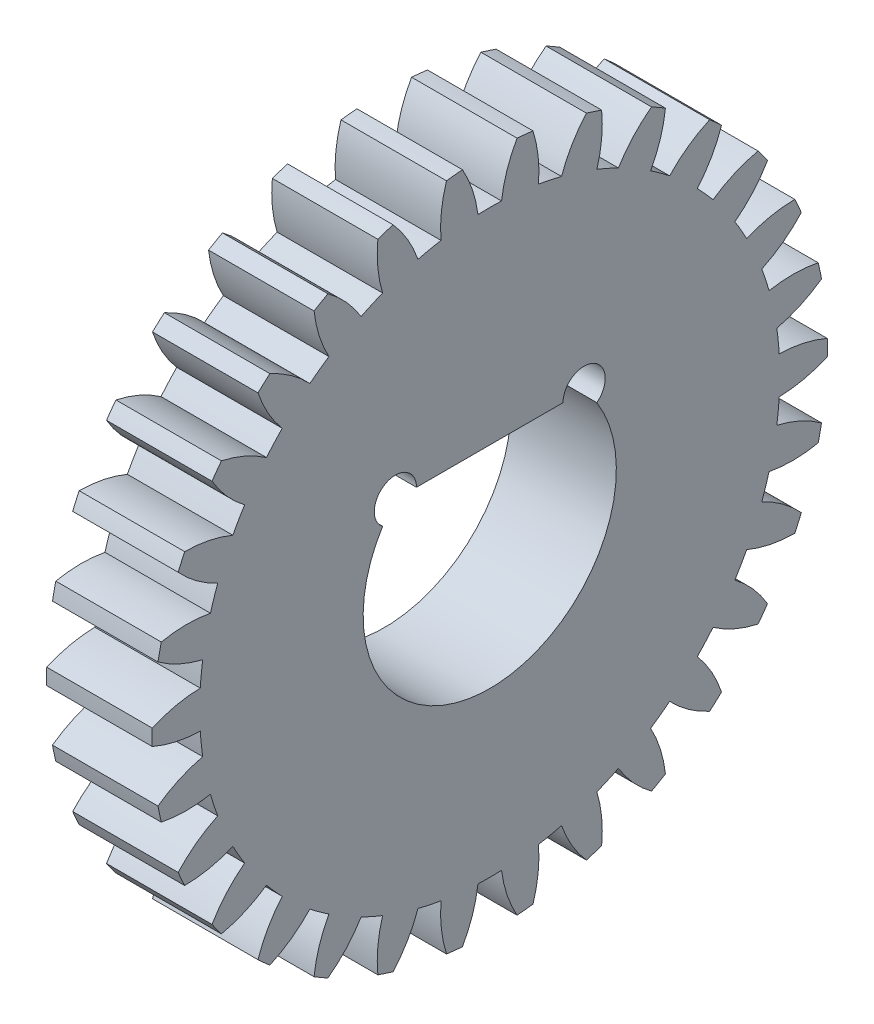
SolidWorks part; units mm, degrees
ref_plane "Plane1" through (0, 0, 0) normal (0, 0, 1) x (1, 0, 0)
ref_plane "Plane2" through (0, 0, 0) normal (0, 1, 0) x (1, 0, 0)
ref_plane "Plane3" through (0, 0, 0) normal (1, 0, 0) x (0, 0, -1)
sketch "HoldingSke" plane through (0, 0, 0) normal (0, 1, 0) x (1, 0, 0)
  line L0 (0, 0) -> (1.7321, -1)
  line L1 (-15, 0) -> (100, 0) construction
  line L2 (0, 0) -> (-2.1039, 2.3779)
  line L3 (0, 0) -> (-11.863, 4.5341)
  line L4 (0, 0) -> (7.479, 4.318)
  line L5 (0, 0) -> (-46.8476, -17.4728)
  line L6 (0, 0) -> (-2.0724, -1.3983)
  line L7 (-2.1039, 2.3779) -> (8.6586, 51.2059)
  line L8 (-76.2, 54.61) -> (-75.2, 54.61)
  line L9 (-67.7845, 28.3722) -> (-49.3413, 33.142)
  line L10 (-76.2, 71.12) -> (104.1128, 71.12)
  line L11 (0, 0) -> (-2.5, 0)
  line L12 (-76.2, 101.6) -> (-76.181, 101.6)
  line L13 (24.9733, 27.94) -> (52.9518, 28.4284)
  line L14 (24.9733, 27.94) -> (24.9743, 27.94)
  line L15 (24.9733, 27.94) -> (100.4006, 29.5858)
  line L16 (-63.627, -0.5) -> (-12.827, -0.5)
  circle A0 centre (0, 0) radius 3
  circle A1 centre (0, 0) radius 6.874
  circle A2 centre (0, 0) radius 37.5
  circle A3 centre (0, 0) radius 3
  dimension "MHD" = 13.748
  dimension "Hub_dia" = 75
  dimension "Bore" = 6
  dimension "MBD" = 6
  dimension "Num_teeth" = 30
  dimension "Pitch" = 2
  dimension "Overall_len" = 50
  dimension "Show_teeth" = 30
  dimension "Thickness" = 2.5
  dimension "OAL" = 50.0001
  dimension "T_dim" = 1
  dimension "Ap" = 14.5
  dimension "H" = 19.05
  dimension "Pitch_radius" = 180.3128
  dimension "Width" = 2.5
  dimension "Backlash" = 0.019
  dimension "Addendum_fac" = 1
  dimension "Dedendum_fac" = 1.25
  dimension "Clearance_fac" = 0.25
  dimension "Dedendum_add" = 0.001
  dimension "Module" = 0.5
sketch "BasProSke" plane through (0, 0, 0) normal (0, 1, 0) x (1, 0, 0)
  line L0 (-10, 0) -> (60, 0) construction
  line L1 (0, 0) -> (0, 8)
  line L2 (0, 0) -> (2.5, 0)
  line L3 (2.5, 0) -> (2.5, 8)
  line L4 (2.5, 8) -> (0, 8)
  dimension "Thickness" = 2.5
  dimension "Diameter" = 16
revolve "Base-Revolve" add sketch "BasProSke" angle 360 about L0
sketch "TooCutSke" plane through (0, 0, 0) normal (1, 0, 0) x (0, 0, -1)
  line L1 (0, 0) -> (0, 107) construction
  line L2 (0, 0) -> (-0.4258, 7.4879) construction
  line L3 (0, 0) -> (-1.5661, 14.9007) construction
  line L4 (-0.4258, 7.4879) -> (-0.7831, 7.4504) construction
  arc A0 (0.279, 6.8683) -> (-0.279, 6.8683) centre (0, 0) ccw
  arc A1 (0.6614, 7.9981) -> (-0.6614, 7.9981) centre (0, 0) ccw
  circle A2 centre (0, 0) radius 7.5 construction
  circle A3 centre (0, 0) radius 7.2611 construction
  arc A4 (-0.279, 6.8683) -> (-0.6614, 7.9981) centre (-3.2551, 6.4906) ccw
  arc A5 (0.6614, 7.9981) -> (0.279, 6.8683) centre (3.2551, 6.4906) ccw
  dimension "Root_dia" = 13.748
  dimension "Overcut_dia" = 16.0508
  dimension "Pitch_dia" = 15
  dimension "Base_dia" = 14.5222
  dimension "Flank_rad" = 3
  dimension "Half_ang" = 6
  dimension "Half_CT" = 0.3593
extrude "ToothCut" cut sketch "TooCutSke" along normal through all
fillet "Breaks" [suppressed] radius 0.01
fillet "RootFillets" [suppressed] radius 0.126
pattern_circular "TeethCuts" count 30 every 12 about axis through (-10, 0, 0) along (1, 0, 0) of "ToothCut", "RootFillets", "Breaks"
sketch "HubNeaOneSke" plane through (0, 0, 0) normal (-1, 0, 0) x (0, 0, 1)
  circle A0 centre (0, 0) radius 6.874
  dimension "Diameter" = 13.748
extrude "HubNearOne" [suppressed] add sketch "HubNeaOneSke" along normal blind 47.5001
sketch "HubNeaBotSke" plane through (0, 0, 0) normal (-1, 0, 0) x (0, 0, 1)
  circle A0 centre (0, 0) radius 6.874
  dimension "Diameter" = 13.748
extrude "HubNearBoth" [suppressed] add sketch "HubNeaBotSke" along normal blind 23.75
ref_plane "FarPln" through (2.5, 0, 0) normal (1, 0, 0) x (0, 0, -1)
sketch "HubFarSke" plane through (2.5, 0, 0) normal (1, 0, 0) x (0, 0, -1)
  circle A0 centre (0, 0) radius 6.874
  dimension "Diameter" = 13.748
extrude "HubFar" [suppressed] add sketch "HubFarSke" along normal blind 23.75
sketch "BorSke" plane through (0, 0, 0) normal (1, 0, 0) x (0, 0, -1)
  circle A0 centre (0, 0) radius 3
  dimension "Diameter" = 6
extrude "Bore" cut sketch "BorSke" along normal mid plane 100.0001
sketch "KeySke" plane through (0, 0, 0) normal (1, 0, 0) x (0, 0, -1)
  line L0 (-1, 0) -> (-1, 4)
  line L1 (-1, 4) -> (1, 4)
  line L2 (1, 4) -> (1, 0)
  line L3 (0, 0) -> (0, 34) construction
  line L4 (-1, 0) -> (1, 0)
  dimension "Offset" = 4
  dimension "Width" = 2
extrude "Keyway" [suppressed] cut sketch "KeySke" along normal mid plane 100.0001
pattern_circular "Keyway2" [suppressed] count 2 every 90 about axis through (-10, 0, 0) along (1, 0, 0)
sketch "草图1" plane through (2.5, 0, 0) normal (1, 0, 0) x (0, 0, -1)
  line L0 (0, 0) -> (0, 2)
  line L1 (-2.2361, 2) -> (2.2361, 2)
  circle A0 centre (0, 0) radius 3 construction
  arc A1 (2.2361, 2) -> (-2.2361, 2) centre (0, 0) ccw
extrude "凸台-拉伸1" add sketch "草图1" against normal through all contours L1 A1
sketch "草图2" plane through (2.5, 0, 0) normal (1, 0, 0) x (0, 0, -1)
  circle A0 centre (2.2361, 2) radius 0.5
  circle A1 centre (-2.2361, 2) radius 0.5
extrude "切除-拉伸1" cut sketch "草图2" against normal through all
equation "' \"Module@HoldingSke\" = 6.35"
equation "' \"Num_teeth@HoldingSke\" = 12"
equation "' \"Ap@HoldingSke\" =  20"
equation "' \"Ap@HoldingSke\" = 20"
equation "' \"Width@HoldingSke\" = 0.5 * 25.4"
equation "' \"Hub_dia@HoldingSke\"= 1 * 25.4"
equation "' \"Hub_dia@HoldingSke\" = 1 * 25.4"
equation "' \"Overall_len@HoldingSke\" = 1.0 * 25.4"
equation "' \"Bore@HoldingSke\" = 0.75 * 25.4"
equation "' \"T_dim@HoldingSke\" = 0.1 * 25.4"
equation "' \"Width@KeySke\" = 0.25 * 25.4"
equation "' \"Show_teeth@HoldingSke\" = 13"
equation "' \"Backlash@HoldingSke\" = 0.009 * 25.4"
equation "' \"Addendum_fac@HoldingSke\" = 1.0"
equation "' \"Dedendum_fac@HoldingSke\" = 1.25"
equation "' \"Dedendum_add@HoldingSke\" = 0.00005 * 25.4"
equation "' \"Clearance_fac@HoldingSke\" = 0.25"
equation "\"Pitch@HoldingSke\" = 1 / \"Module@HoldingSke\""
equation "\"Overcut_dia@TooCutSke\" = (\"Num_teeth@HoldingSke\" + 2 * \"Addendum_fac@HoldingSke\") / \"Pitch@HoldingSke\" + 0.002 * 25.4"
equation "\"Pitch_dia@TooCutSke\" = \"Num_teeth@HoldingSke\" / \"Pitch@HoldingSke\""
equation "\"Base_dia@TooCutSke\" = \"Num_teeth@HoldingSke\" / \"Pitch@HoldingSke\" * cos((\"Ap@HoldingSke\"  * 3.14159265 / 180))"
equation "\"Root_dia@TooCutSke\" = (\"Num_teeth@HoldingSke\" + 2) / \"Pitch@HoldingSke\" - 2 * (\"Addendum_fac@HoldingSke\" + \"Dedendum_fac@HoldingSke\") / \"Pitch@HoldingSke\" - \"Dedendum_add@HoldingSke\" * 2"
equation "\"Half_ang@TooCutSke\" = 180 / \"Num_teeth@HoldingSke\""
equation "\"Half_CT@TooCutSke\" = \"Num_teeth@HoldingSke\" / \"Pitch@HoldingSke\" * sin((3.14159265 / 2 / \"Num_teeth@HoldingSke\")) / 2 - 7 * \"Backlash@HoldingSke\" / 4"
equation "\"Flank_rad@TooCutSke\" = \"Num_teeth@HoldingSke\" / \"Pitch@HoldingSke\" / 5"
equation "\"Radius@RootFillets\" = \"Clearance_fac@HoldingSke\" / \"Pitch@HoldingSke\" + \"Dedendum_add@HoldingSke\""
equation "\"Break_rad@Breaks\" = 0.02 / \"Pitch@HoldingSke\""
equation "\"Thickness@HoldingSke\" = \"Width@HoldingSke\""
equation "\"OAL@HoldingSke\" = \"Thickness@HoldingSke\""
equation "\"MHD@HoldingSke\" = (\"Num_teeth@HoldingSke\" + 2) / \"Pitch@HoldingSke\" - 2 * (\"Addendum_fac@HoldingSke\" + \"Dedendum_fac@HoldingSke\")  / \"Pitch@HoldingSke\" - \"Dedendum_add@HoldingSke\" * 2"
equation "\"MBD@HoldingSke\" = (\"Num_teeth@HoldingSke\" + 2) / \"Pitch@HoldingSke\" - 2 * (\"Addendum_fac@HoldingSke\" + \"Dedendum_fac@HoldingSke\")  / \"Pitch@HoldingSke\" - \"Dedendum_add@HoldingSke\" * 2 - 0.002 * 25.4"
equation "\"MHD@HoldingSke\" = ((sgn( \"MHD@HoldingSke\" - \"Hub_dia@HoldingSke\" )-1)*( \"MHD@HoldingSke\" - \"Hub_dia@HoldingSke\" ))/-2+ \"Hub_dia@HoldingSke\""
equation "\"MBD@HoldingSke\" = ((sgn( \"MBD@HoldingSke\" - \"Bore@HoldingSke\" )-1)*( \"MBD@HoldingSke\" - \"Bore@HoldingSke\" ))/-2+ \"Bore@HoldingSke\""
equation "\"OAL@HoldingSke\" = ((sgn( \"OAL@HoldingSke\" - \"Overall_len@HoldingSke\" )+1)*( \"OAL@HoldingSke\" - \"Overall_len@HoldingSke\" ))/2 + \"Overall_len@HoldingSke\" + 0.000002 * 25.4"
equation "\"Num_teeth@TeethCuts\" = int( \"Show_teeth@HoldingSke\" ) + 1"
equation "\"Num_teeth@TeethCuts\" = ((sgn( \"Num_teeth@TeethCuts\" - \"Num_teeth@HoldingSke\" )-1)*( \"Num_teeth@TeethCuts\" - \"Num_teeth@HoldingSke\" ))/-2+ \"Num_teeth@HoldingSke\""
equation "\"Num_teeth@TeethCuts\" = ((sgn( \"Num_teeth@TeethCuts\" - 2.0)+1)*( \"Num_teeth@TeethCuts\" - 2.0))/2 +2.0"
equation "\"Angle@TeethCuts\" = 360.0 / \"Num_teeth@HoldingSke\""
equation "\"Diameter@BasProSke\" = (\"Num_teeth@HoldingSke\" + 2 * \"Addendum_fac@HoldingSke\") / \"Pitch@HoldingSke\""
equation "\"Thickness@BasProSke\"  = \"Thickness@HoldingSke\""
equation "' \"Fillet_rad@BasProSke\" =  \"Thickness@HoldingSke\" * 0.05"
equation "' \"Fillet_rad@BasProSke\" = \"Thickness@HoldingSke\" * 0.05"
equation "\"MHD@HoldingSke\" = ((sgn( \"MHD@HoldingSke\" - \"Root_dia@TooCutSke\" )-1)*( \"MHD@HoldingSke\" - \"Root_dia@TooCutSke\" ))/-2+ \"Root_dia@TooCutSke\""
equation "\"Diameter@HubNeaOneSke\" = \"MHD@HoldingSke\""
equation "\"Length@HubNearOne\" = \"OAL@HoldingSke\" - \"Thickness@BasProSke\""
equation "\"Diameter@HubNeaBotSke\" = \"MHD@HoldingSke\""
equation "\"Length@HubNearBoth\" = ( \"OAL@HoldingSke\" - \"Thickness@BasProSke\" ) / 2.0"
equation "\"Thickness@FarPln\" = \"Thickness@BasProSke\""
equation "\"Diameter@HubFarSke\" = \"MHD@HoldingSke\""
equation "\"Length@HubFar\" = ( \"OAL@HoldingSke\" - \"Thickness@BasProSke\" ) / 2.0"
equation "\"Diameter@BorSke\" = \"MBD@HoldingSke\""
equation "\"D1@Bore\" = \"OAL@HoldingSke\" * 2.0"
equation "\"D1@Keyway\" = \"OAL@HoldingSke\" * 2.0"
equation "\"Offset@KeySke\" = \"T_dim@HoldingSke\" + \"MBD@HoldingSke\" / 2.0"
